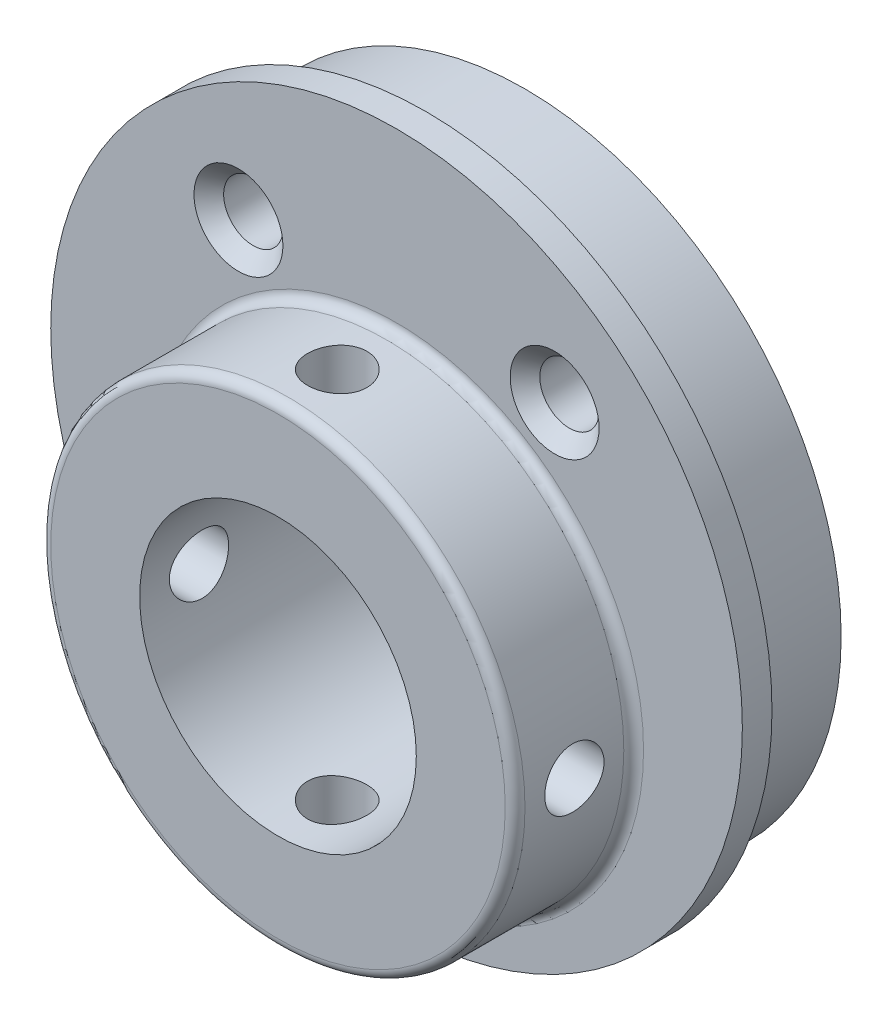
SolidWorks part; units mm, degrees
ref_plane "Front Plane" through (0, 0, 0) normal (0, 0, 1) x (1, 0, 0)
ref_plane "Top Plane" through (0, 0, 0) normal (0, 1, 0) x (1, 0, 0)
ref_plane "Right Plane" through (0, 0, 0) normal (1, 0, 0) x (0, 0, -1)
sketch "Sketch1" plane through (0, 0, 0) normal (0, 0, 1) x (1, 0, 0)
  circle A0 centre (0, 0) radius 17.5
  dimension "D1" = 35
extrude "Boss-Extrude1" add sketch "Sketch1" along normal blind 1.5
sketch "Sketch2" plane through (0, 0, 1.5) normal (0, 0, 1) x (1, 0, 0)
  circle A0 centre (0, 0) radius 16
  dimension "D1" = 32
extrude "Boss-Extrude2" add sketch "Sketch2" against normal blind 5 from surface at -1.5 starting at face at (17.5, 0, 0)
sketch "Sketch3" plane through (0, 0, 1.5) normal (0, 0, 1) x (1, 0, 0)
  circle A0 centre (0, -3.5) radius 12
  dimension "D1" = 24
  dimension "D2" = 3.5
extrude "Boss-Extrude3" add sketch "Sketch3" along normal blind 6
sketch "Sketch4" plane through (0, 0, 7.5) normal (0, 0, 1) x (1, 0, 0)
  circle A0 centre (0, -3.5) radius 7
  dimension "D1" = 14
extrude "Cut-Extrude1" cut sketch "Sketch4" against normal through all
sketch "Sketch5" plane through (0, 0, 1.5) normal (0, 0, 1) x (1, 0, 0)
  circle A0 centre (-8, 9.5) radius 1.5
  circle A1 centre (8, 9.5) radius 1.5
  dimension "D1" = 3
  dimension "D2" = 3
  dimension "D3" = 8
  dimension "D4" = 8
  dimension "D5" = 9.5
extrude "Cut-Extrude2" cut sketch "Sketch5" against normal through all
chamfer "Chamfer1" distance 0.75 angle 45 2 edges at (9.5, 9.5, 1.5) (-6.5, 9.5, 1.5)
fillet "Fillet1" radius 0.5 2 edges at (12, -3.5, 7.5) (12, -3.5, 1.5)
sketch "Sketch6" plane through (0, 0, 0) normal (1, 0, 0) x (0, 0, -1)
  line L0 (5, -16) -> (5, 16) construction
  line L1 (-2, 8.5) -> (-7, 8.5) construction
  circle A0 centre (-4.5, -3.5) radius 1.5
  dimension "D1" = 3
  dimension "D2" = 9.5
  dimension "D3" = 12
extrude "Cut-Extrude3" cut sketch "Sketch6" against normal through all both and the other way through all
pattern_circular "CirPattern1" count 4 over 360 about axis through (0, -3.5, 7.5) along (0, 0, -1) of "Cut-Extrude3"
